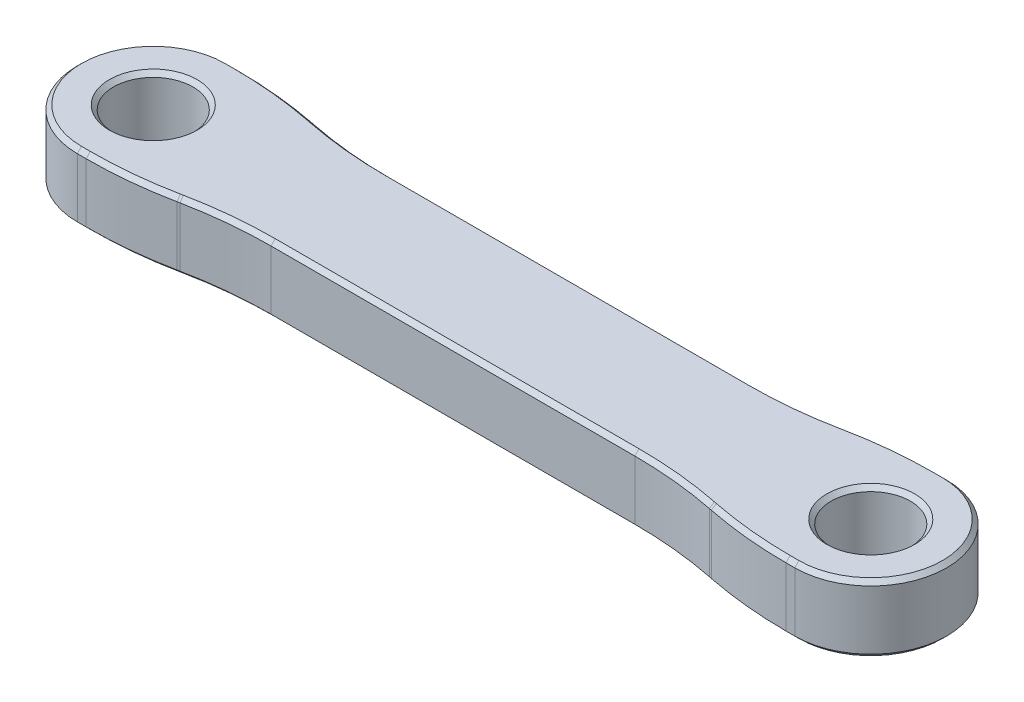
SolidWorks part; units mm, degrees
ref_plane "Front Plane" through (0, 0, 0) normal (0, 0, 1) x (1, 0, 0)
ref_plane "Top Plane" through (0, 0, 0) normal (0, 1, 0) x (1, 0, 0)
ref_plane "Right Plane" through (0, 0, 0) normal (1, 0, 0) x (0, 0, -1)
sketch "Sketch1" plane through (0, 0, 0) normal (0, 1, 0) x (1, 0, 0)
  line L0 (6, 9) -> (16, 7)
  line L1 (0, 9) -> (6, 9)
  line L3 (0, -9) -> (6, -9)
  line L5 (16, 7) -> (69, 7)
  line L6 (69, 7) -> (79, 9)
  line L7 (6, -9) -> (16, -7)
  line L8 (16, -7) -> (69, -7)
  line L9 (69, -7) -> (79, -9)
  line L10 (79, 9) -> (85, 9)
  line L11 (79, -9) -> (85, -9)
  circle A0 centre (0, 0) radius 4.7
  arc A1 (0, 9) -> (0, -9) centre (0, 0) ccw
  circle A2 centre (85, 0) radius 4.7
  arc A3 (85, -9) -> (85, 9) centre (85, 0) ccw
  point P15 (18.263, 5.0649)
  point P18 (0, 0)
  point P19 (0, 0)
  point P20 (0, 0)
  point P21 (17.289, -5.7468)
  point P22 (0, 0)
  point P23 (0, 0)
  point P24 (73.1981, 5)
  point P25 (15.0487, 5)
  dimension "D1" = 9.4
  dimension "D2" = 18
  dimension "D3" = 85
  dimension "D4" = 2
  dimension "D5" = 6
  dimension "D6" = 6
  dimension "D7" = 10
extrude "Boss-Extrude1" add sketch "Sketch1" along normal blind 8
fillet "Fillet1" radius 50 4 edges at (69, 4, 7) (16, 4, 7) (69, 4, -7) (16, 4, -7)
fillet "Fillet2" radius 50 4 edges at (79, 4, -9) (6, 4, -9) (79, 4, 9) (6, 4, 9)
chamfer "Chamfer1" distance 0.5 angle 45 4 edges at (0, 0, 4.7) (85, 0, 4.7) (85, 8, 4.7) (0, 8, 4.7)
chamfer "Chamfer2" distance 0.5 angle 45 40 edges at (42.5, 0, -7) (16.0241, 0, -7.2433) (68.9759, 0, -7.2433) (5.9759, 0, -8.7567) (79.0241, 0, -8.7567) (0.5245, 0, -9) (84.4755, 0, -9) (-9, 0, 0) (94, 0, 0) (0.5245, 0, 9) (84.4755, 0, 9) (5.9759, 0, 8.7567) (79.0241, 0, 8.7567) (16.0241, 0, 7.2433) (68.9759, 0, 7.2433) (42.5, 0, 7) (42.5, 8, -7) (16.0241, 8, -7.2433) (68.9759, 8, -7.2433) (5.9759, 8, -8.7567) (79.0241, 8, -8.7567) (0.5245, 8, -9) (84.4755, 8, -9) (-9, 8, 0) (94, 8, 0) (0.5245, 8, 9) (84.4755, 8, 9) (5.9759, 8, 8.7567) (79.0241, 8, 8.7567) (16.0241, 8, 7.2433) (68.9759, 8, 7.2433) (42.5, 8, 7) (11, 0, -8) (74, 0, -8) (11, 0, 8) (74, 0, 8) (11, 8, -8) (74, 8, -8) (11, 8, 8) (74, 8, 8)
